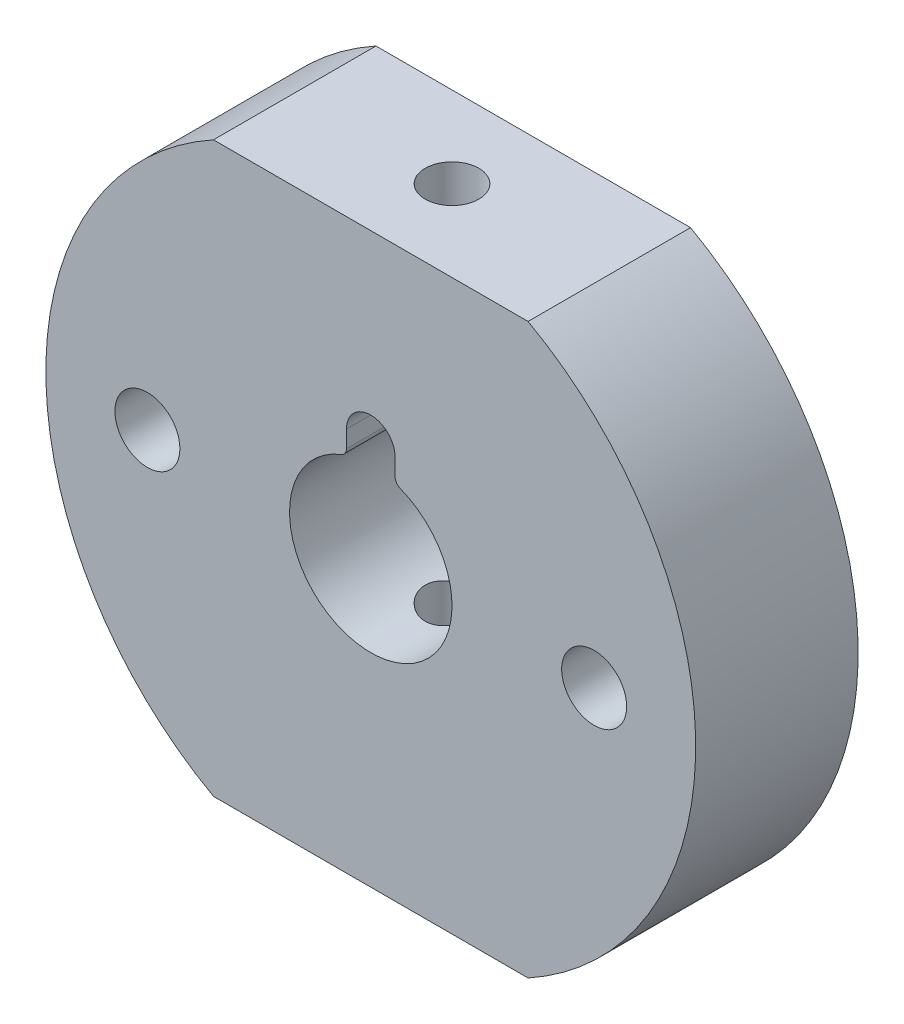
SolidWorks part; units mm, degrees
material "1023 炭素鋼板 (SS)"
ref_plane "正面" through (0, 0, 0) normal (0, 0, 1) x (1, 0, 0)
ref_plane "平面" through (0, 0, 0) normal (0, 1, 0) x (1, 0, 0)
ref_plane "右側面" through (0, 0, 0) normal (1, 0, 0) x (0, 0, -1)
sketch "ｽｹｯﾁ1" plane through (0, 0, 0) normal (0, 0, 1) x (1, 0, 0)
  line L0 (-20, 0) -> (20, 0) construction
  circle A0 centre (0, 0) radius 20
  circle A1 centre (0, 0) radius 5
  circle A2 centre (-13.75, 0) radius 2
  circle A3 centre (13.75, 0) radius 2
  dimension "D1" = 40
  dimension "D2" = 10
  dimension "D3" = 4
  dimension "D4" = 4
  dimension "D5" = 27.5
  dimension "D6" = 13.75
extrude "ﾎﾞｽ - 押し出し1" add sketch "ｽｹｯﾁ1" along normal blind 10
sketch "ｽｹｯﾁ2" plane through (0, 0, 0) normal (0, 1, 0) x (1, 0, 0)
  line L0 (0, 0) -> (0, -10) construction
  line L1 (-20, -10) -> (20, -10) construction
  circle A0 centre (0, -5) radius 1.65
  dimension "D1" = 3.3
extrude "ｶｯﾄ - 押し出し1" cut sketch "ｽｹｯﾁ2" against normal through all both and the other way through all
sketch "ｽｹｯﾁ3" plane through (0, 0, 10) normal (0, 0, 1) x (1, 0, 0)
  line L0 (0, 0) -> (0, 50000)
  line L2 (-1.5, 4.7697) -> (1.5, 4.7697)
  line L3 (-1.5, 4.7697) -> (-1.5, 6.1697)
  line L4 (-1.5, 6.1697) -> (1.5, 6.1697)
  line L5 (1.5, 4.7697) -> (1.5, 6.1697)
  circle A0 centre (0, 0) radius 5 construction
  circle A1 centre (0, 6.1697) radius 1.5
  circle M8 centre (0, 0) radius 5
  dimension "D1" = 1.4
  dimension "D2" = 3
extrude "ｶｯﾄ - 押し出し2" cut sketch "ｽｹｯﾁ3" against normal through all contours L4 A1 L0 M8 | L0 A1 L4 | L4 A1 L0 | A1 L5 M8 | A1 L4 L0 M8 | A1 L3 M8
sketch "ｽｹｯﾁ4" plane through (0, 0, 10) normal (0, 0, 1) x (1, 0, 0)
  line L0 (0, 0) -> (0, -20) construction
  line L1 (-9.6825, -17.5) -> (9.6825, -17.5)
  line L2 (0, 0) -> (20, 0) construction
  line L3 (-9.6825, 17.5) -> (9.6825, 17.5)
  circle A0 centre (0, 0) radius 20 construction
  circle A2 centre (0, 0) radius 20
  circle A3 centre (0, 0) radius 20
  point P8 (0, -17.5)
  circle M11 centre (0, 0) radius 20
  dimension "D2" = 17.5
  dimension "D1" = 0
extrude "ｶｯﾄ - 押し出し3" cut sketch "ｽｹｯﾁ4" against normal through all contours L3 M11 | L1 M11
fillet "ﾌｨﾚｯﾄ1" radius 0.5 2 edges at (1.5, 4.7697, 7.8437) (-1.5, 4.7697, 7.8437)
